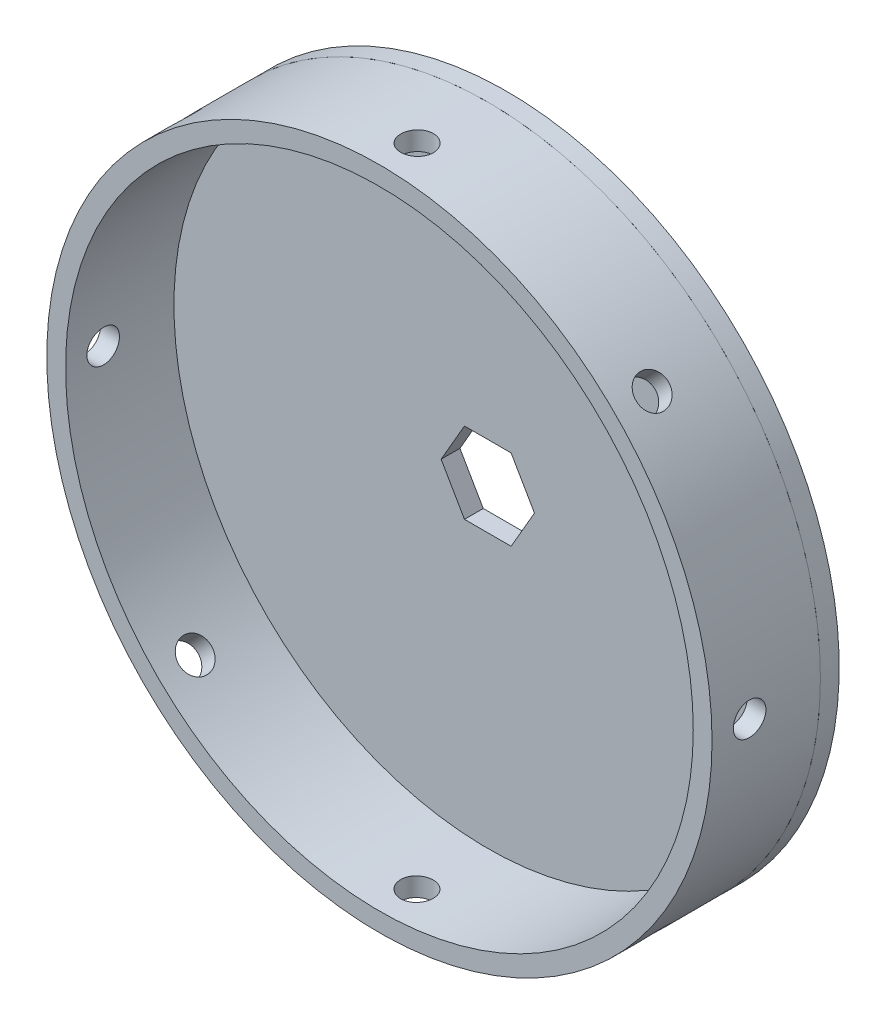
SolidWorks part; units mm, degrees
ref_plane "前视基准面" through (0, 0, 0) normal (0, 0, 1) x (1, 0, 0)
ref_plane "上视基准面" through (0, 0, 0) normal (0, 1, 0) x (1, 0, 0)
ref_plane "右视基准面" through (0, 0, 0) normal (1, 0, 0) x (0, 0, -1)
sketch "草图1" plane through (0, 0, 0) normal (0, 0, 1) x (1, 0, 0)
  circle A0 centre (0, 0) radius 53.1
  circle A1 centre (0, 0) radius 50.1
  dimension "D1" = 100.2
  dimension "D2" = 3
extrude "凸台-拉伸1" add sketch "草图1" along normal blind 22.3
sketch "草图2" plane through (0, 0, 0) normal (0, 0, -1) x (-1, 0, 0)
  circle A0 centre (0, 0) radius 53.1
extrude "凸台-拉伸2" add sketch "草图2" along normal blind 3
sketch "草图3" plane through (0, 0, -3) normal (0, 0, -1) x (-1, 0, 0)
  line L0 (0, 53.1) -> (0, -53.1) construction
  line L1 (53.1, 0) -> (-53.1, 0) construction
  line L3 (3.7239, -6.45) -> (7.4478, 0)
  line L4 (7.4478, 0) -> (3.7239, 6.45)
  line L5 (3.7239, 6.45) -> (-3.7239, 6.45)
  line L6 (-3.7239, 6.45) -> (-7.4478, 0)
  line L7 (-7.4478, 0) -> (-3.7239, -6.45)
  line L8 (-3.7239, -6.45) -> (3.7239, -6.45)
  circle A0 centre (0, 0) radius 53.1 construction
  circle A1 centre (0, 0) radius 6.45 construction
  dimension "D1" = 12.9
ref_plane "基准面4" through (0, 53.1, 0) normal (0, 1, 0) x (1, 0, 0)
sketch "草图4" plane through (0, 53.1, 0) normal (0, 1, 0) x (1, 0, 0)
  line L0 (0, 0) -> (0, -26.2496) construction
  line L1 (-53.1, -22.3) -> (53.1, -22.3) construction
  circle A0 centre (0, -11.3) radius 2.6
  dimension "D1" = 5.2
  dimension "D2" = 11
extrude "切除-拉伸3" cut sketch "草图4" against normal through all
pattern_circular "阵列(圆周)1" count 8 over 360 about axis through (0, 0, -3) along (0, 0, -1) of "切除-拉伸3"
extrude "切除-拉伸4" cut sketch "草图3" against normal blind 10
sketch "草图5" plane through (0, 0, 22.3) normal (0, 0, 1) x (1, 0, 0)
  circle A0 centre (0, 0) radius 65.354
extrude "切除-拉伸5" cut sketch "草图5" against normal blind 5
